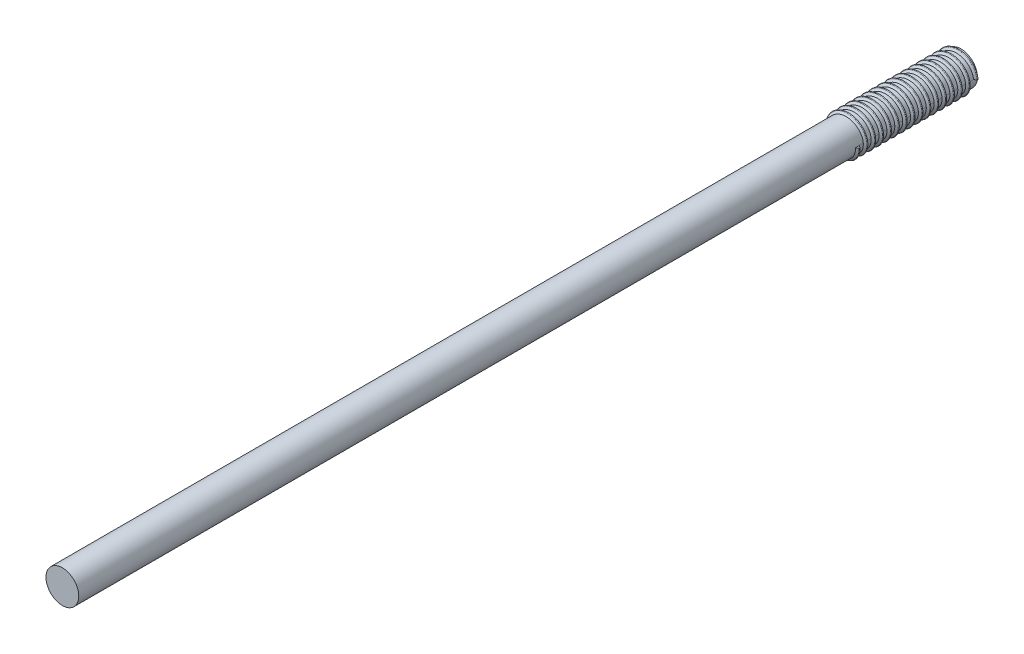
SolidWorks part; units mm, degrees
ref_plane "Front Plane" through (0, 0, 0) normal (0, 0, 1) x (1, 0, 0)
ref_plane "Top Plane" through (0, 0, 0) normal (0, 1, 0) x (1, 0, 0)
ref_plane "Right Plane" through (0, 0, 0) normal (1, 0, 0) x (0, 0, -1)
sketch "Sketch1" plane through (0, 0, 0) normal (0, 0, 1) x (1, 0, 0)
  circle A0 centre (0, 0) radius 1.25
extrude "Extrude1" add sketch "Sketch1" against normal blind 65 and the other way blind 3.5
sketch "Sketch2" plane through (0, 0, -65) normal (0, 0, -1) x (-1, 0, 0)
  circle A0 centre (0, 0) radius 1.25
curve "Helix/Spiral1" pitch 0.6 height 9 turns 15
sketch "Sketch3" plane through (0, 0, 0) normal (0, 1, 0) x (1, 0, 0)
  line L0 (1.2326, 65) -> (1.2326, 64.6838)
  line L1 (1.25, 65) -> (-1.25, 65) construction
  line L2 (1.2326, 64.6838) -> (1.4087, 64.7945)
  line L3 (1.4104, 64.878) -> (1.2326, 65)
  arc A0 (1.4087, 64.7945) -> (1.4104, 64.878) centre (1.3821, 64.8368) ccw
  dimension "D1" = 0.05
sweep "Sweep1" add profiles "Sketch3" path "Helix/Spiral1"
